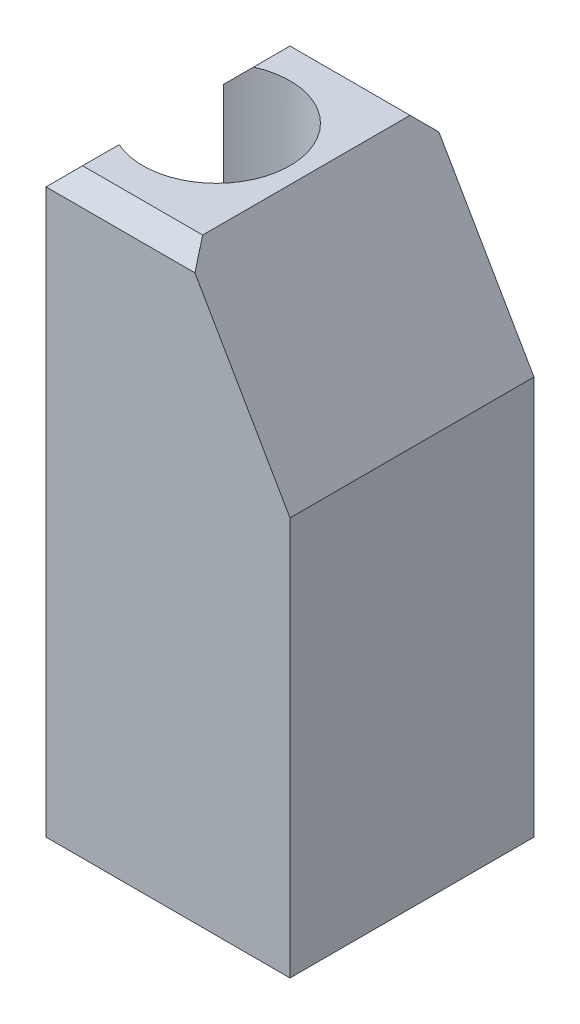
SolidWorks part; units mm, degrees
ref_plane "Front Plane" through (0, 0, 0) normal (0, 0, 1) x (1, 0, 0)
ref_plane "Top Plane" through (0, 0, 0) normal (0, 1, 0) x (1, 0, 0)
ref_plane "Right Plane" through (0, 0, 0) normal (1, 0, 0) x (0, 0, -1)
sketch "Sketch1" plane through (0, 0, 0) normal (0, 1, 0) x (1, 0, 0)
  line L1 (-20, 20) -> (20, 20)
  line L2 (-20, 20) -> (-20, -20)
  line L3 (-20, -20) -> (20, -20)
  line L4 (20, 20) -> (20, -20)
  line L5 (-20, 20) -> (20, -20) construction
  line L6 (-20, -20) -> (20, 20) construction
  point P0 (0, 0)
  dimension "D1" = 40
  dimension "D2" = 40
extrude "Boss-Extrude1" add sketch "Sketch1" along normal blind 35.33
sketch "Sketch2" plane through (0, 35.33, 0) normal (0, 1, 0) x (1, 0, 0)
  circle A0 centre (-12.07, 0) radius 12.07
  dimension "D1" = 24.14
  dimension "D2" = 12.07
extrude "Cut-Extrude1" cut sketch "Sketch2" against normal blind 42
sketch "Sketch3" plane through (0, 0, 0) normal (0, -1, 0) x (1, 0, 0)
  line L1 (20, 20) -> (-20, 20)
  line L2 (20, 20) -> (20, -20)
  line L3 (20, -20) -> (-20, -20)
  line L4 (-20, 20) -> (-20, -20)
extrude "Boss-Extrude2" add sketch "Sketch3" along normal blind 60
chamfer "Chamfer1" distance 30 angle 30 1 edges at (20, 35.33, 0)
chamfer "Chamfer2" distance 3 angle 45 4 edges at (-20, 35.33, -14.5497) (-8.6603, 35.33, -20) (-20, 35.33, 14.5497) (-8.6603, 35.33, 20)
